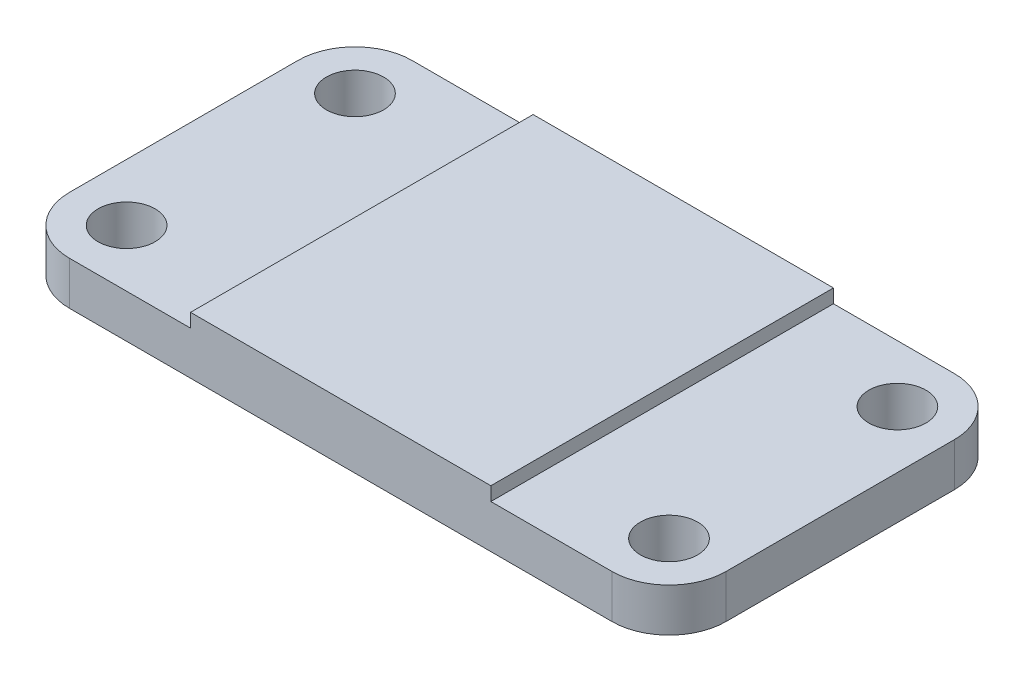
SolidWorks part; units mm, degrees
material "Nylon 101"
ref_plane "Front Plane" through (0, 0, 0) normal (0, 0, 1) x (1, 0, 0)
ref_plane "Top Plane" through (0, 0, 0) normal (0, 1, 0) x (1, 0, 0)
ref_plane "Right Plane" through (0, 0, 0) normal (1, 0, 0) x (0, 0, -1)
sketch "Sketch1" plane through (0, 0, 0) normal (0, 1, 0) x (1, 0, 0)
  line L1 (-73.025, -38.1) -> (73.025, -38.1)
  line L2 (-73.025, -38.1) -> (-73.025, 38.1)
  line L3 (-73.025, 38.1) -> (73.025, 38.1)
  line L4 (73.025, -38.1) -> (73.025, 38.1)
  line L5 (-73.025, -38.1) -> (73.025, 38.1) construction
  line L6 (-73.025, 38.1) -> (73.025, -38.1) construction
  point P0 (0, 0)
  dimension "D1" = 146.05
  dimension "D2" = 76.2
extrude "Boss-Extrude1" add sketch "Sketch1" along normal blind 9.652
sketch "Sketch2" plane through (0, 9.652, 0) normal (0, 1, 0) x (1, 0, 0)
  line L0 (-73.025, -38.1) -> (73.025, -38.1) construction
  line L1 (-33.401, 38.1) -> (33.401, 38.1)
  line L2 (-33.401, 38.1) -> (-33.401, -38.1)
  line L3 (-33.401, -38.1) -> (33.401, -38.1)
  line L4 (33.401, 38.1) -> (33.401, -38.1)
  line L5 (-33.401, 38.1) -> (33.401, -38.1) construction
  line L6 (-33.401, -38.1) -> (33.401, 38.1) construction
  line L7 (73.025, -38.1) -> (73.025, 38.1) construction
  point P0 (0, 0)
  dimension "D1" = 39.624
extrude "Boss-Extrude2" add sketch "Sketch2" along normal blind 3.048
fillet "Fillet1" radius 12.7 4 edges at (-73.025, 4.826, -38.1) (-73.025, 4.826, 38.1) (73.025, 4.826, -38.1) (73.025, 4.826, 38.1)
hole_wizard "3/8 (0.5) Diameter Hole1" positions "Sketch3" profile "Sketch4" hole size "3/8" standard "ANSI Inch" end condition through all
sketch "Sketch3" plane through (0, 9.652, 0) normal (0, 1, 0) x (1, 0, 0)
  point P0 (-60.325, 25.4)
  point P3 (-60.325, -25.4)
  point P6 (60.325, -25.4)
  point P9 (60.325, 25.4)
sketch "Sketch4" plane through (-60.325, 9.652, -25.4) normal (1, 0, 0) x (0, 0, 1)
  line L0 (0, 0) -> (0, 9.652)
  line L1 (0, 9.652) -> (6.35, 9.652)
  line L2 (6.35, 9.652) -> (6.35, 0)
  line L5 (6.35, 0) -> (0, 0)
  line L11 (0, -6.35) -> (0, 107.95) construction
  dimension "Thru Hole Dia." = 12.7
  dimension "Thru Hole Depth" = 9.652
